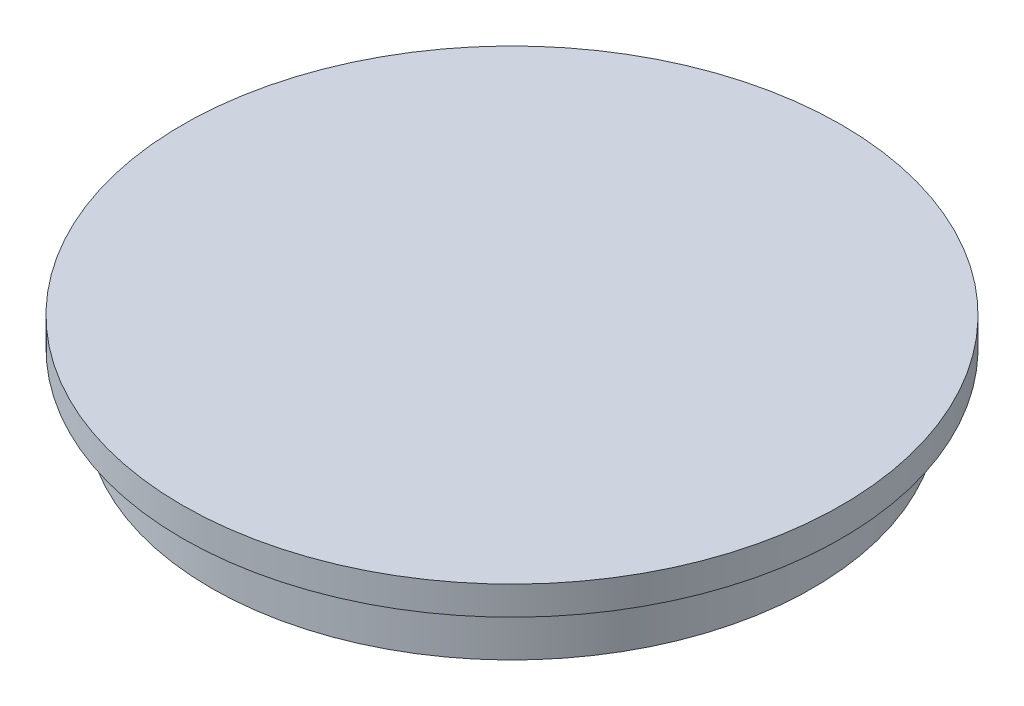
SolidWorks part; units mm, degrees
ref_plane "Front Plane" through (0, 0, 0) normal (0, 0, 1) x (1, 0, 0)
ref_plane "Top Plane" through (0, 0, 0) normal (0, 1, 0) x (1, 0, 0)
ref_plane "Right Plane" through (0, 0, 0) normal (1, 0, 0) x (0, 0, -1)
sketch "Sketch1" plane through (0, 0, 0) normal (0, 1, 0) x (1, 0, 0)
  circle A0 centre (0, 0) radius 29.21
  dimension "D1" = 58.42
extrude "Boss-Extrude2" add sketch "Sketch1" along normal blind 2.54
sketch "Sketch2" plane through (0, 0, 0) normal (0, -1, 0) x (1, 0, 0)
  circle A0 centre (0, 0) radius 26.67
  circle A1 centre (0, 0) radius 22.86
  dimension "D1" = 53.34
  dimension "D2" = 3.81
extrude "Boss-Extrude3" add sketch "Sketch2" along normal blind 5.08
